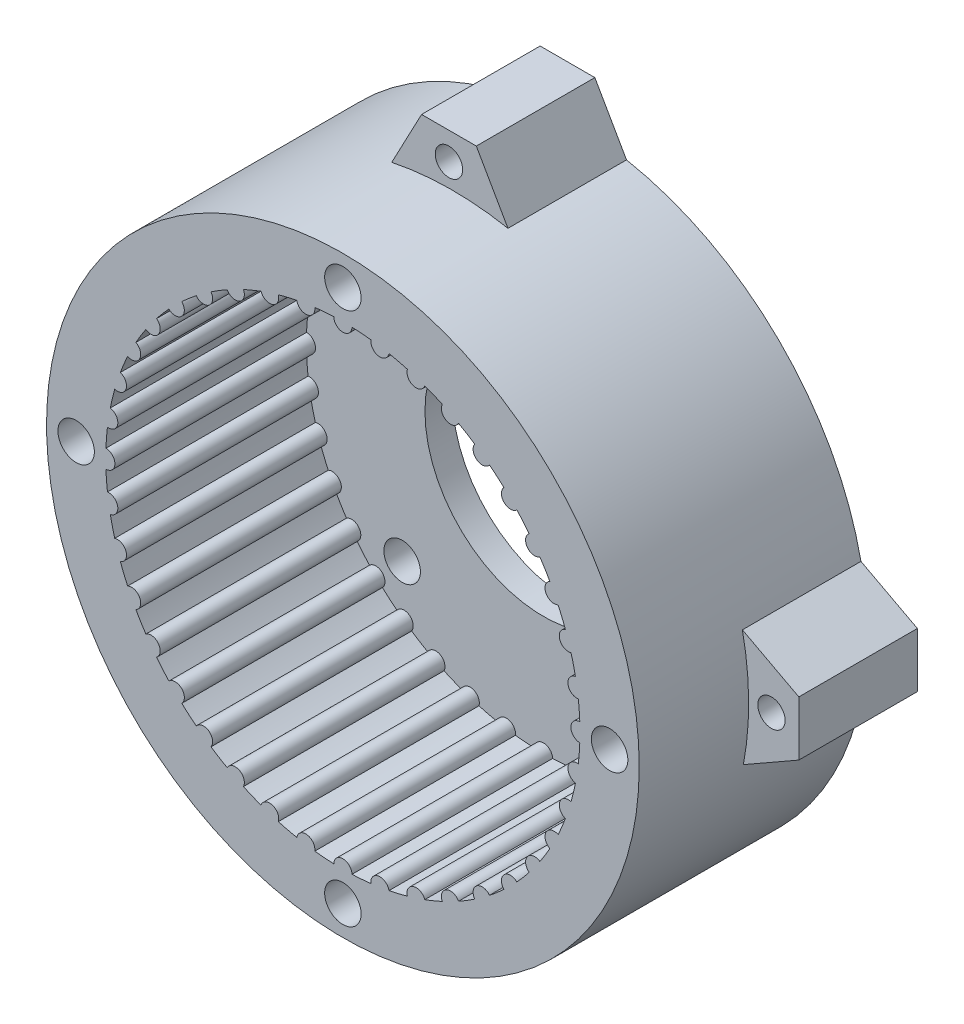
SolidWorks part; units mm, degrees
ref_plane "Plan de face" through (0, 0, 0) normal (0, 0, 1) x (1, 0, 0)
ref_plane "Plan de dessus" through (0, 0, 0) normal (0, 1, 0) x (1, 0, 0)
ref_plane "Plan de droite" through (0, 0, 0) normal (1, 0, 0) x (0, 0, -1)
sketch "Esquisse2" plane through (0, 0, 0) normal (0, 0, 1) x (1, 0, 0)
  circle A0 centre (0, 0) radius 32.5
  dimension "D1" = 65
extrude "Boss.-Extru.1" add sketch "Esquisse2" along normal blind 25
sketch "Esquisse3" plane through (0, 0, 25) normal (0, 0, 1) x (1, 0, 0)
  circle A0 centre (0, 26) radius 1
  circle A1 centre (4.0673, 25.6799) radius 1
  circle A2 centre (8.0344, 24.7275) radius 1
  circle A3 centre (11.8038, 23.1662) radius 1
  circle A4 centre (15.2824, 21.0344) radius 1
  circle A5 centre (18.3848, 18.3848) radius 1
  circle A6 centre (21.0344, 15.2824) radius 1
  circle A7 centre (23.1662, 11.8038) radius 1
  circle A8 centre (24.7275, 8.0344) radius 1
  circle A9 centre (25.6799, 4.0673) radius 1
  circle A10 centre (26, 0) radius 1
  circle A11 centre (25.6799, -4.0673) radius 1
  circle A12 centre (24.7275, -8.0344) radius 1
  circle A13 centre (23.1662, -11.8038) radius 1
  circle A14 centre (21.0344, -15.2824) radius 1
  circle A15 centre (18.3848, -18.3848) radius 1
  circle A16 centre (15.2824, -21.0344) radius 1
  circle A17 centre (11.8038, -23.1662) radius 1
  circle A18 centre (8.0344, -24.7275) radius 1
  circle A19 centre (4.0673, -25.6799) radius 1
  circle A20 centre (0, -26) radius 1
  circle A21 centre (-4.0673, -25.6799) radius 1
  circle A22 centre (-8.0344, -24.7275) radius 1
  circle A23 centre (-11.8038, -23.1662) radius 1
  circle A24 centre (-15.2824, -21.0344) radius 1
  circle A25 centre (-18.3848, -18.3848) radius 1
  circle A26 centre (-21.0344, -15.2824) radius 1
  circle A27 centre (-23.1662, -11.8038) radius 1
  circle A28 centre (-24.7275, -8.0344) radius 1
  circle A29 centre (-25.6799, -4.0673) radius 1
  circle A30 centre (-26, 0) radius 1
  circle A31 centre (-25.6799, 4.0673) radius 1
  circle A32 centre (-24.7275, 8.0344) radius 1
  circle A33 centre (-23.1662, 11.8038) radius 1
  circle A34 centre (-21.0344, 15.2824) radius 1
  circle A35 centre (-18.3848, 18.3848) radius 1
  circle A36 centre (-15.2824, 21.0344) radius 1
  circle A37 centre (-11.8038, 23.1662) radius 1
  circle A38 centre (-8.0344, 24.7275) radius 1
  circle A39 centre (-4.0673, 25.6799) radius 1
  point P81 (0, 0)
  dimension "D1" = 2
  dimension "D2" = 26
  dimension "D3" = 40
extrude "Enlèv. mat.-Extru.1" cut sketch "Esquisse3" against normal blind 24
sketch "Esquisse4" plane through (0, 0, 25) normal (0, 0, 1) x (1, 0, 0)
  circle A0 centre (0, 0) radius 26
  dimension "D1" = 52
extrude "Enlèv. mat.-Extru.2" cut sketch "Esquisse4" against normal blind 22
sketch "Esquisse5" plane through (0, 0, 3) normal (0, 0, 1) x (1, 0, 0)
  circle A0 centre (0, 0) radius 13
  dimension "D1" = 26
extrude "Enlèv. mat.-Extru.3" cut sketch "Esquisse5" against normal through all contours A0
sketch "Esquisse6" plane through (0, 0, 3) normal (0, 0, 1) x (1, 0, 0)
  circle A0 centre (-15.5, 15.5) radius 2
  circle A1 centre (15.5, 15.5) radius 2
  circle A2 centre (15.5, -15.5) radius 2
  circle A3 centre (-15.5, -15.5) radius 2
  dimension "D1" = 4
  dimension "D2" = 4
  dimension "D3" = 4
  dimension "D4" = 4
  dimension "D5" = 31
  dimension "D6" = 31
  dimension "D7" = 31
  dimension "D8" = 15.5
  dimension "D9" = 15.5
extrude "Enlèv. mat.-Extru.4" cut sketch "Esquisse6" against normal through all
sketch "Esquisse7" plane through (0, 0, 1) normal (0, 0, 1) x (1, 0, 0)
  circle A0 centre (-21.0344, 15.2824) radius 1
extrude "Boss.-Extru.2" add sketch "Esquisse7" along normal blind 24
pattern_circular "Répétition circulaire1" count 40 every 9 about axis through (0, 0, 0) along (0, 0, 1) of "Boss.-Extru.2"
sketch "Esquisse8" plane through (0, 0, 25) normal (0, 0, 1) x (1, 0, 0)
  circle A0 centre (0, 29.25) radius 2
  dimension "D1" = 4
  dimension "D2" = 29.25
extrude "Enlèv. mat.-Extru.5" cut sketch "Esquisse8" against normal blind 7
pattern_circular "Répétition circulaire2" count 4 every 90 about axis through (0, 0, 0) along (0, 0, 1) of "Enlèv. mat.-Extru.5"
sketch "Esquisse9" plane through (0, 0, 0) normal (0, 0, -1) x (-1, 0, 0)
  circle A0 centre (0, 28) radius 2
  dimension "D1" = 4
  dimension "D2" = 28
extrude "Enlèv. mat.-Extru.6" cut sketch "Esquisse9" against normal blind 7 contours A0
pattern_circular "Répétition circulaire3" count 4 every 90 about axis through (0, 0, 0) along (0, 0, 1) of "Enlèv. mat.-Extru.6"
ref_plane "Plan1" through (0, 0, 13) normal (0, 0, 1) x (1, 0, 0)
sketch "Esquisse11" plane through (0, 0, 13) normal (0, 0, 1) x (1, 0, 0)
  line L0 (-6.6441, 31.8136) -> (-3.3686, 38)
  line L1 (-3.3686, 38) -> (2.6314, 38)
  line L2 (2.6314, 38) -> (6.1034, 31.9218)
  circle A0 centre (0, 0) radius 32.5 construction
  arc A1 (-6.6441, 31.8136) -> (6.1034, 31.9218) centre (0, 0) cw
  circle A2 centre (-0.3686, 34.9981) radius 1.5
  dimension "D5" = 3
  dimension "D1" = 6
  dimension "D2" = 7
  dimension "D3" = 7
  dimension "D4" = 38
  dimension "D6" = 35
  dimension "D7" = 3
extrude "Boss.-Extru.3" add sketch "Esquisse11" against normal up to surface (13 mm away) contours L0 L1 L2 A1 | A2 up to face at (-28, -2, 0)
pattern_circular "Répétition circulaire5" count 4 every 90 about axis through (0, 0, 0) along (0, 0, 1) of "Boss.-Extru.3"
